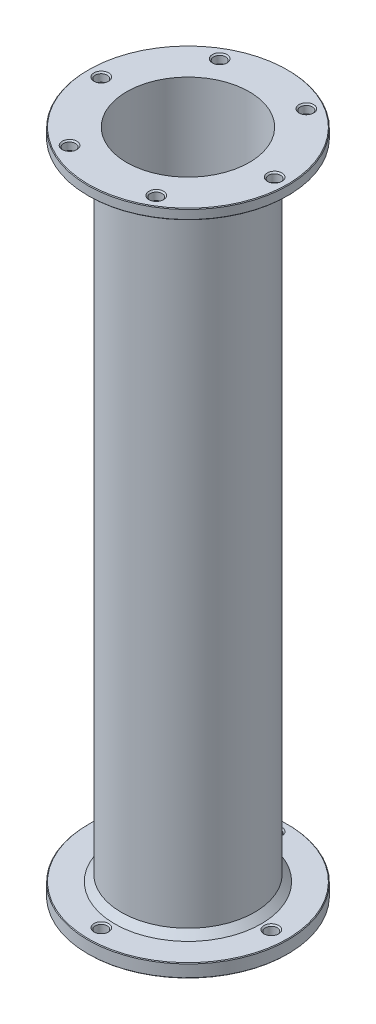
SolidWorks part; units mm, degrees
material "1.0045 (S355JR)"
ref_plane "Ebene vorne" through (0, 0, 0) normal (0, 0, 1) x (1, 0, 0)
ref_plane "Ebene oben" through (0, 0, 0) normal (0, 1, 0) x (1, 0, 0)
ref_plane "Ebene rechts" through (0, 0, 0) normal (1, 0, 0) x (0, 0, -1)
sketch "Skizze1" plane through (0, 0, 0) normal (0, 1, 0) x (1, 0, 0)
  line L0 (0, 0) -> (0, 130) construction
  circle A0 centre (0, 0) radius 150
  circle A1 centre (0, 0) radius 92
  circle A2 centre (0, 130) radius 9
  circle A3 centre (125, 0) radius 9
  circle A4 centre (-5, -125) radius 9
  circle A5 centre (-130, 5) radius 9
  point P15 (-2.5, 2.5)
  dimension "D1" = 300
  dimension "D2" = 18
  dimension "D5" = 184
  dimension "D3" = 130
  dimension "D4" = 4
extrude "Aufsatz-Linear austragen1" add sketch "Skizze1" along normal blind 20
sketch "Skizze2" plane through (0, 20, 0) normal (0, 1, 0) x (1, 0, 0)
  circle A0 centre (0, 0) radius 100
  circle A1 centre (0, 0) radius 92 construction
  circle A2 centre (0, 0) radius 92
  dimension "D1" = 200
extrude "Aufsatz-Linear austragen2" add sketch "Skizze2" along normal blind 965
sketch "Skizze3" plane through (0, 985, 0) normal (0, 1, 0) x (1, 0, 0)
  line L0 (130, 0) -> (0, 0) construction
  circle A0 centre (0, 0) radius 92 construction
  circle A1 centre (0, 0) radius 92
  circle A2 centre (130, 0) radius 9
  circle A6 centre (0, 0) radius 150
  circle A7 centre (65, -112.5833) radius 9
  circle A8 centre (-65, -112.5833) radius 9
  circle A9 centre (-130, 0) radius 9
  circle A10 centre (-65, 112.5833) radius 9
  circle A11 centre (65, 112.5833) radius 9
  point P18 (0, 0)
  dimension "D3" = 18
  dimension "D4" = 300
  dimension "D1" = 130
  dimension "D2" = 6
extrude "Aufsatz-Linear austragen3" add sketch "Skizze3" along normal blind 15
chamfer "Fase1" distance 10 angle 45 2 edges at (0, 985, 100) (0, 20, 100)
chamfer "Fase2" distance 1 angle 45 4 edges at (0, 0, 150) (0, 20, 150) (0, 985, 150) (0, 1000, 150)
chamfer "Fase3" distance 2 angle 45 20 edges at (-5, 0, 134) (-5, 20, 134) (-130, 0, 4) (-130, 20, 4) (0, 0, -121) (0, 20, -121) (125, 0, 9) (125, 20, 9) (-65, 985, -103.5833) (-65, 1000, -103.5833) (-130, 985, 9) (-130, 1000, 9) (-65, 985, 121.5833) (-65, 1000, 121.5833) (65, 985, 121.5833) (65, 1000, 121.5833) (130, 985, 9) (130, 1000, 9) (65, 985, -103.5833) (65, 1000, -103.5833)
equation "\"D5@Skizze1\"=200-2*8"
